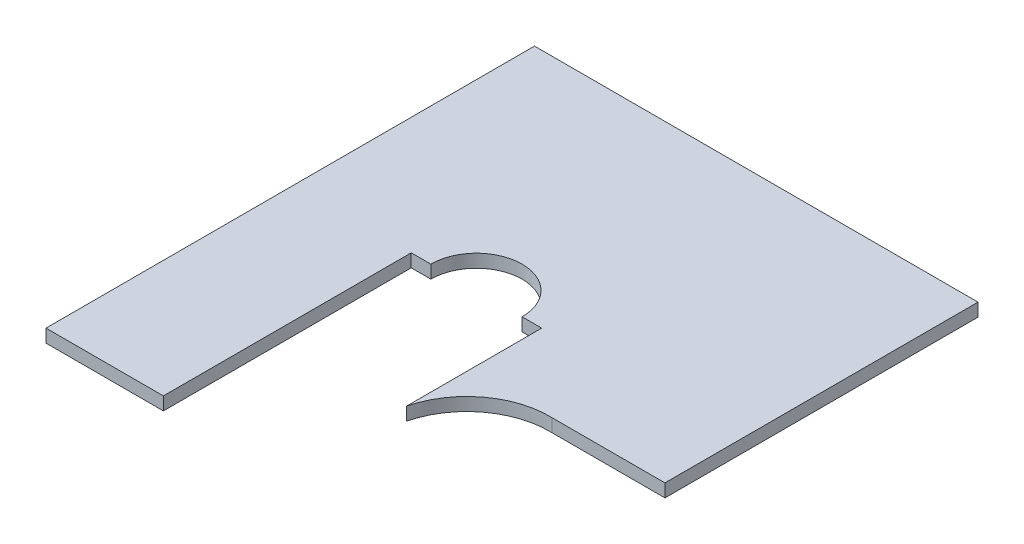
SolidWorks part; units mm, degrees
ref_plane "Front Plane" through (0, 0, 0) normal (0, 0, 1) x (1, 0, 0)
ref_plane "Top Plane" through (0, 0, 0) normal (0, 1, 0) x (1, 0, 0)
ref_plane "Right Plane" through (0, 0, 0) normal (1, 0, 0) x (0, 0, -1)
sketch "Sketch1" plane through (0, 0, 0) normal (0, 1, 0) x (1, 0, 0)
  line L8 (1.9771, 26.1187) -> (1.9771, 38.1187)
  line L9 (1.9771, 38.1187) -> (-15.0229, 38.1187)
  line L10 (-15.0229, 38.1187) -> (-15.0229, 19.3936)
  line L15 (-2.3479, 26.1187) -> (1.9771, 26.1187)
  line L19 (-10.5229, 19.3936) -> (-15.0229, 19.3936)
  line L20 (-10.5229, 28.8936) -> (-9.7729, 28.8936)
  line L27 (-5.5229, 28.8936) -> (-5.5229, 23.7186)
  line L30 (-10.5229, 28.8936) -> (-10.5229, 19.3936)
  line L31 (-6.2729, 28.8936) -> (-5.5229, 28.8936)
  arc A3 (-2.3479, 26.1187) -> (-5.5229, 23.7186) centre (-2.4435, 22.9452) ccw
  arc A4 (-6.2729, 28.8936) -> (-9.7729, 28.8936) centre (-8.0229, 28.8936) ccw
  dimension "D6" = 3.5
  dimension "D7" = 3.175
  dimension "D1" = 4.325
  dimension "D2" = 12
  dimension "D3" = 17
  dimension "D5" = 7
extrude "Boss-Extrude1" add sketch "Sketch1" along normal mid plane 0.5
